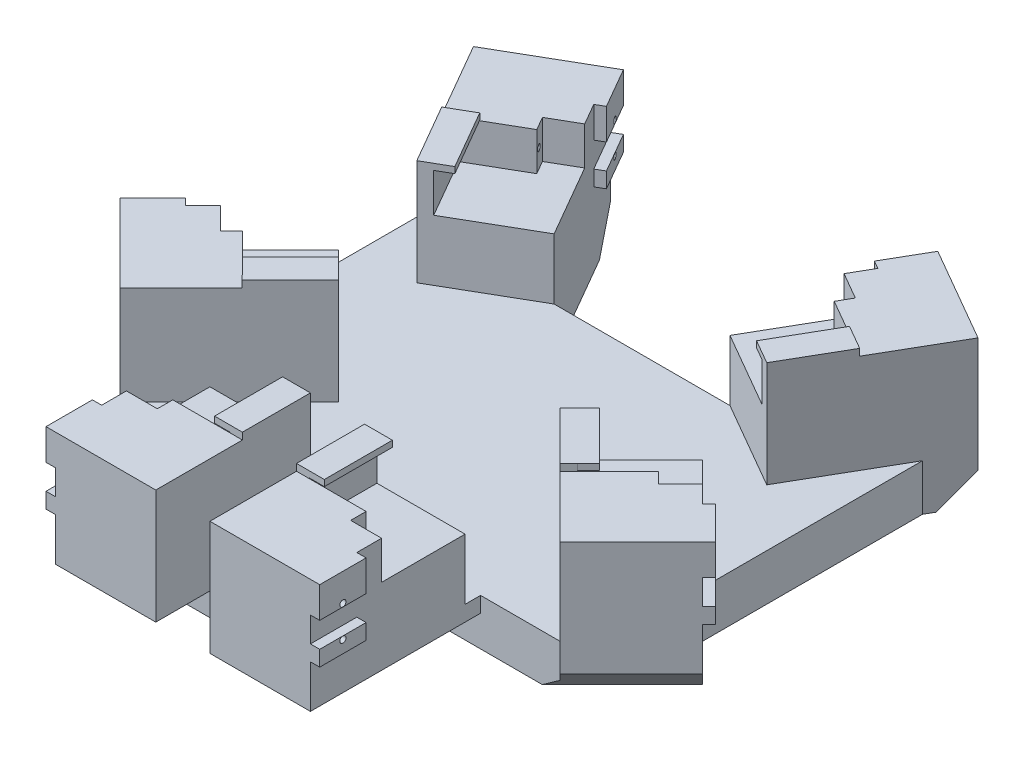
SolidWorks part; units mm, degrees
ref_plane "Front Plane" through (0, 0, 0) normal (0, 0, 1) x (1, 0, 0)
ref_plane "Top Plane" through (0, 0, 0) normal (0, 1, 0) x (1, 0, 0)
ref_plane "Right Plane" through (0, 0, 0) normal (1, 0, 0) x (0, 0, -1)
sketch "Sketch1" plane through (0, 0, 0) normal (0, 1, 0) x (1, 0, 0)
  line L1 (-75, 75) -> (75, 75)
  line L2 (-75, 75) -> (-75, -75)
  line L3 (-75, -75) -> (75, -75)
  line L4 (75, 75) -> (75, -75)
  line L5 (-75, 75) -> (75, -75) construction
  line L6 (-75, -75) -> (75, 75) construction
  point P0 (0, 0)
  dimension "D1" = 150
extrude "Base" add sketch "Sketch1" along normal mid plane 15 contours L2 L3 L4 L1
sketch "Sketch2" plane through (0, 7.5, 0) normal (0, 1, 0) x (1, 0, 0)
  line L0 (0, 93.5371) -> (0, -100.4541) construction
  line L2 (-41.25, -95) -> (-8.75, -95)
  line L3 (-41.25, -95) -> (-41.25, -45)
  line L4 (-41.25, -45) -> (-8.75, -45)
  line L5 (-8.75, -95) -> (-8.75, -45)
  line L6 (-41.25, -95) -> (-8.75, -45) construction
  line L7 (-41.25, -45) -> (-8.75, -95) construction
  line L8 (-75, -75) -> (75, -75) construction
  line L12 (-75, 75) -> (75, 75) construction
  line L13 (-81.5729, 80.5256) -> (-53.4271, 96.7756)
  line L14 (-81.5729, 80.5256) -> (-28.4271, 53.4744) construction
  line L15 (-28.4271, 53.4744) -> (-53.4271, 96.7756)
  line L16 (-56.5729, 37.2244) -> (-28.4271, 53.4744)
  line L17 (-56.5729, 37.2244) -> (-81.5729, 80.5256)
  line L18 (-56.5729, 37.2244) -> (-53.4271, 96.7756) construction
  line L25 (-58.8128, 14.1682) -> (-35.8318, -8.8128)
  line L26 (-58.8128, 14.1682) -> (-71.1872, -44.1682) construction
  line L27 (-71.1872, -44.1682) -> (-35.8318, -8.8128)
  line L28 (-94.1682, -21.1872) -> (-71.1872, -44.1682)
  line L29 (-94.1682, -21.1872) -> (-58.8128, 14.1682)
  line L30 (-94.1682, -21.1872) -> (-35.8318, -8.8128) construction
  line L36 (-75, 75) -> (-75, -75) construction
  point P3 (-25, -70)
  point P13 (-55, 67)
  point P23 (-65, -15)
  dimension "D2" = 32.5
  dimension "D3" = 30
  dimension "D4" = 32.5
  dimension "D5" = 50
  dimension "D6" = 32.5
  dimension "D7" = 50
  dimension "D8" = 130
  dimension "D9" = 60
  dimension "D10" = 50
  dimension "D11" = 30
  dimension "D12" = 110
  dimension "D13" = 45
  dimension "D14" = 8
  dimension "D15" = 50
extrude "ModelServos" add sketch "Sketch2" along normal blind 22 contours L28 L27 L25 L29
mirror "Mirror1" about plane through (0, 0, 0) normal (1, 0, 0) of "ModelServos"
sketch "Sketch3" plane through (0, 7.5, 0) normal (0, 1, 0) x (1, 0, 0)
  line L1 (75, -40) -> (41.25, -40)
  line L2 (75, -40) -> (75, -75)
  line L3 (75, -75) -> (41.25, -75)
  line L4 (41.25, -40) -> (41.25, -75)
  line L6 (41.25, -45) -> (41.25, -75) construction
  line L7 (-75, -75) -> (75, -75) construction
  line L8 (75, -40.3553) -> (75, -75) construction
  dimension "D1" = 35
extrude "Cut-Extrude1" cut sketch "Sketch3" against normal through all
mirror "Mirror2" about plane through (0, 0, 0) normal (1, 0, 0) of "Cut-Extrude1"
sketch "Sketch5" plane through (0, 29.5, 0) normal (0, 1, 0) x (1, 0, 0)
  line L0 (12.75, -45) -> (12.75, -67)
  line L1 (8.75, -45) -> (41.25, -45) construction
  line L2 (12.75, -67) -> (41.25, -67)
  line L3 (41.25, -45) -> (41.25, -95) construction
  line L4 (12.75, -45) -> (41.25, -45)
  line L5 (41.25, -45) -> (41.25, -67)
  dimension "D1" = 22
  dimension "D2" = 28.5
extrude "Cut-Extrude3" cut sketch "Sketch5" against normal blind 2.35
sketch "Sketch6" plane through (0, 29.5, 0) normal (0, 1, 0) x (1, 0, 0)
  line L0 (41.25, -67) -> (41.25, -95) construction
  line L1 (41.25, -80) -> (38.25, -80)
  line L2 (41.25, -80) -> (41.25, -95)
  line L3 (41.25, -95) -> (38.25, -95)
  line L4 (38.25, -80) -> (38.25, -95)
  line L5 (41.25, -95) -> (8.75, -95) construction
  dimension "D1" = 3
  dimension "D2" = 15
extrude "Boss-Extrude1" add sketch "Sketch6" along normal blind 10
sketch "Sketch8" plane through (41.25, 0, 0) normal (1, 0, 0) x (0, 0, -1)
  line L1 (-95, 39.5) -> (-80, 39.5)
  line L2 (-95, 39.5) -> (-95, 29.5)
  line L3 (-95, 29.5) -> (-80, 29.5)
  line L4 (-80, 39.5) -> (-80, 29.5)
extrude "Boss-Extrude2" add sketch "Sketch8" along normal blind 3
sketch "Sketch9" plane through (41.25, 0, 0) normal (1, 0, 0) x (0, 0, -1)
  line L1 (-95, 21.4) -> (-80, 21.4)
  line L2 (-95, 21.4) -> (-95, 16.4)
  line L3 (-95, 16.4) -> (-80, 16.4)
  line L4 (-80, 21.4) -> (-80, 16.4)
  line L6 (-95, 29.5) -> (-95, 7.5) construction
  dimension "D1" = 15
  dimension "D2" = 5
  dimension "D3" = 8.1
extrude "Boss-Extrude3" add sketch "Sketch9" along normal blind 3
sketch "Sketch10" plane through (0, 29.5, 0) normal (0, 1, 0) x (1, 0, 0)
  line L0 (58.8128, 14.1682) -> (38.6603, -5.9844)
  line L1 (35.8318, -8.8128) -> (58.8128, 14.1682) construction
  line L2 (38.6603, -5.9844) -> (54.2166, -21.5407)
  line L3 (54.2166, -21.5407) -> (74.3692, -1.3882)
  line L4 (58.8128, 14.1682) -> (94.1682, -21.1872) construction
  line L5 (74.3692, -1.3882) -> (58.8128, 14.1682)
  dimension "D1" = 28.5
  dimension "D2" = 22
extrude "Cut-Extrude4" cut sketch "Sketch10" against normal blind 2.35
sketch "Sketch11" plane through (0, 29.5, 0) normal (0, 1, 0) x (1, 0, 0)
  line L0 (94.1682, -21.1872) -> (89.9255, -25.4298)
  line L1 (94.1682, -21.1872) -> (71.1872, -44.1682) construction
  line L2 (89.9255, -25.4298) -> (79.3189, -14.8232)
  line L3 (79.3189, -14.8232) -> (83.5616, -10.5806)
  line L4 (74.3692, -1.3882) -> (94.1682, -21.1872) construction
  line L5 (83.5616, -10.5806) -> (94.1682, -21.1872)
  dimension "D1" = 15
  dimension "D2" = 6
extrude "Boss-Extrude4" add sketch "Sketch11" along normal blind 10
sketch "Sketch12" plane through (36.4905, 0, -36.4905) normal (0.7071, 0, -0.7071) x (-0.7071, 0, -0.7071)
  line L1 (-66.5685, 29.5) -> (-81.5685, 29.5)
  line L2 (-66.5685, 29.5) -> (-66.5685, 39.5)
  line L3 (-66.5685, 39.5) -> (-81.5685, 39.5)
  line L4 (-81.5685, 29.5) -> (-81.5685, 39.5)
extrude "Boss-Extrude5" add sketch "Sketch12" along normal blind 3
sketch "Sketch13" plane through (36.4905, 0, -36.4905) normal (0.7071, 0, -0.7071) x (-0.7071, 0, -0.7071)
  line L0 (-81.5685, 29.5) -> (-81.5685, 7.5) construction
  line L1 (-81.5685, 21.4) -> (-66.5685, 21.4)
  line L2 (-81.5685, 21.4) -> (-81.5685, 16.4)
  line L3 (-81.5685, 16.4) -> (-66.5685, 16.4)
  line L4 (-66.5685, 21.4) -> (-66.5685, 16.4)
  dimension "D1" = 15
  dimension "D2" = 5
  dimension "D3" = 8.1
extrude "Boss-Extrude6" add sketch "Sketch13" along normal blind 3
sketch "Sketch14" plane through (0, 7.5, 0) normal (0, 1, 0) x (1, 0, 0)
  line L0 (-28.4271, 53.4744) -> (28.4271, 53.4744)
  line L1 (28.4271, 53.4744) -> (40.8549, 75)
  line L2 (40.8549, 75) -> (-40.8549, 75)
  line L3 (-40.8549, 75) -> (-28.4271, 53.4744)
extrude "Cut-Extrude5" cut sketch "Sketch14" against normal through all
sketch "Sketch15" plane through (0, 29.5, 0) normal (0, 1, 0) x (1, 0, 0)
  line L0 (28.4271, 53.4744) -> (39.4271, 72.5269)
  line L1 (28.4271, 53.4744) -> (53.4271, 96.7756) construction
  line L2 (39.4271, 72.5269) -> (64.1088, 58.2769)
  line L3 (64.1088, 58.2769) -> (53.1088, 39.2244)
  line L4 (56.5729, 37.2244) -> (28.4271, 53.4744) construction
  line L5 (53.1088, 39.2244) -> (28.4271, 53.4744)
  dimension "D1" = 22
  dimension "D2" = 28.5
extrude "Cut-Extrude6" cut sketch "Sketch15" against normal blind 2.35
sketch "Sketch16" plane through (0, 29.5, 0) normal (0, 1, 0) x (1, 0, 0)
  line L0 (53.4271, 96.7756) -> (58.6232, 93.7756)
  line L1 (53.4271, 96.7756) -> (81.5729, 80.5256) construction
  line L2 (58.6232, 93.7756) -> (51.1232, 80.7853)
  line L3 (51.1232, 80.7853) -> (45.9271, 83.7853)
  line L4 (39.4271, 72.5269) -> (53.4271, 96.7756) construction
  line L5 (45.9271, 83.7853) -> (53.4271, 96.7756)
  dimension "D1" = 15
  dimension "D2" = 6
extrude "Boss-Extrude7" add sketch "Sketch16" along normal blind 10
sketch "Sketch17" plane through (-1.8348, 0, -1.0593) normal (-0.866, 0, -0.5) x (-0.5, 0, 0.866)
  line L1 (-95.5237, 29.5) -> (-110.5237, 29.5)
  line L2 (-95.5237, 29.5) -> (-95.5237, 39.5)
  line L3 (-95.5237, 39.5) -> (-110.5237, 39.5)
  line L4 (-110.5237, 29.5) -> (-110.5237, 39.5)
extrude "Boss-Extrude8" add sketch "Sketch17" along normal blind 3
sketch "Sketch18" plane through (-1.8348, 0, -1.0593) normal (-0.866, 0, -0.5) x (-0.5, 0, 0.866)
  line L0 (-110.5237, 29.5) -> (-110.5237, 7.5) construction
  line L1 (-110.5237, 21.4) -> (-95.5237, 21.4)
  line L2 (-110.5237, 21.4) -> (-110.5237, 16.4)
  line L3 (-110.5237, 16.4) -> (-95.5237, 16.4)
  line L4 (-95.5237, 21.4) -> (-95.5237, 16.4)
  dimension "D1" = 15
  dimension "D2" = 5
  dimension "D3" = 8.1
extrude "Boss-Extrude9" add sketch "Sketch18" along normal blind 3
sketch "Sketch20" plane through (0, 29.5, 0) normal (0, 1, 0) x (1, 0, 0)
  line L12 (41.25, -67) -> (12.75, -67)
  line L17 (12.75, -67) -> (12.75, -45)
  line L18 (12.75, -45) -> (8.75, -45)
  line L19 (8.75, -45) -> (8.75, -95)
  line L20 (8.75, -95) -> (38.25, -95)
  line L21 (38.25, -95) -> (38.25, -80)
  line L22 (38.25, -80) -> (41.25, -80)
  line L23 (41.25, -80) -> (41.25, -67)
  line L24 (41.25, -67) -> (12.75, -67)
  line L29 (12.75, -67) -> (12.75, -45)
  line L30 (12.75, -45) -> (8.75, -45)
  line L31 (8.75, -45) -> (8.75, -95)
  line L32 (8.75, -95) -> (38.25, -95)
  line L33 (38.25, -95) -> (38.25, -80)
  line L34 (38.25, -80) -> (41.25, -80)
  line L35 (41.25, -80) -> (41.25, -67)
  dimension "D1" = 0
extrude "Boss-Extrude10" add sketch "Sketch20" along normal up to surface (10 mm away) up to face at (41.25, 39.5, 87.5)
sketch "Sketch22" plane through (0, 29.5, 0) normal (0, 1, 0) x (1, 0, 0)
  line L12 (74.3692, -1.3882) -> (54.2166, -21.5407)
  line L17 (54.2166, -21.5407) -> (38.6603, -5.9844)
  line L18 (38.6603, -5.9844) -> (35.8318, -8.8128)
  line L19 (35.8318, -8.8128) -> (71.1872, -44.1682)
  line L20 (71.1872, -44.1682) -> (89.9255, -25.4298)
  line L21 (89.9255, -25.4298) -> (79.3189, -14.8232)
  line L22 (79.3189, -14.8232) -> (83.5616, -10.5806)
  line L23 (83.5616, -10.5806) -> (74.3692, -1.3882)
  line L24 (74.3692, -1.3882) -> (54.2166, -21.5407)
  line L29 (54.2166, -21.5407) -> (38.6603, -5.9844)
  line L30 (38.6603, -5.9844) -> (35.8318, -8.8128)
  line L31 (35.8318, -8.8128) -> (71.1872, -44.1682)
  line L32 (71.1872, -44.1682) -> (89.9255, -25.4298)
  line L33 (89.9255, -25.4298) -> (79.3189, -14.8232)
  line L34 (79.3189, -14.8232) -> (83.5616, -10.5806)
  line L35 (83.5616, -10.5806) -> (74.3692, -1.3882)
  dimension "D1" = 0
extrude "Boss-Extrude11" add sketch "Sketch22" along normal up to surface (10 mm away) up to face at (87.8042, 39.5, 16.9445)
sketch "Sketch24" plane through (0, 29.5, 0) normal (0, 1, 0) x (1, 0, 0)
  line L14 (39.4271, 72.5269) -> (64.1088, 58.2769)
  line L15 (64.1088, 58.2769) -> (53.1088, 39.2244)
  line L16 (53.1088, 39.2244) -> (56.5729, 37.2244)
  line L17 (56.5729, 37.2244) -> (81.5729, 80.5256)
  line L18 (81.5729, 80.5256) -> (58.6232, 93.7756)
  line L19 (58.6232, 93.7756) -> (51.1232, 80.7853)
  line L20 (51.1232, 80.7853) -> (45.9271, 83.7853)
  line L21 (45.9271, 83.7853) -> (39.4271, 72.5269)
  line L26 (39.4271, 72.5269) -> (64.1088, 58.2769)
  line L27 (64.1088, 58.2769) -> (53.1088, 39.2244)
  line L28 (53.1088, 39.2244) -> (56.5729, 37.2244)
  line L29 (56.5729, 37.2244) -> (81.5729, 80.5256)
  line L30 (81.5729, 80.5256) -> (58.6232, 93.7756)
  line L31 (58.6232, 93.7756) -> (51.1232, 80.7853)
  line L32 (51.1232, 80.7853) -> (45.9271, 83.7853)
  line L33 (45.9271, 83.7853) -> (39.4271, 72.5269)
  dimension "D1" = 0
extrude "Boss-Extrude12" add sketch "Sketch24" along normal up to surface (10 mm away) up to face at (50.9761, 39.5, -89.5304)
sketch "Sketch27" plane through (0, 7.5, 0) normal (0, -1, 0) x (1, 0, 0)
  line L4 (8.75, 75) -> (41.25, 75)
  line L5 (41.25, 75) -> (41.25, 95)
  line L6 (41.25, 95) -> (8.75, 95)
  line L7 (8.75, 95) -> (8.75, 75)
  line L8 (8.75, 75) -> (41.25, 75)
  line L9 (41.25, 75) -> (41.25, 95)
  line L10 (41.25, 95) -> (8.75, 95)
  line L11 (8.75, 95) -> (8.75, 75)
  dimension "D1" = 0
extrude "Boss-Extrude15" add sketch "Sketch27" along normal up to surface (15 mm away) up to face at (0, -7.5, -8.0791)
sketch "Sketch26" plane through (0, 7.5, 0) normal (0, -1, 0) x (1, 0, 0)
  line L3 (94.1682, 21.1872) -> (71.1872, 44.1682)
  line L4 (75, 40) -> (75, 2.019)
  line L5 (75, 2.019) -> (94.1682, 21.1872)
  line L6 (94.1682, 21.1872) -> (71.1872, 44.1682)
  line L7 (75, 40) -> (75, 2.019)
  line L8 (75, 2.019) -> (94.1682, 21.1872)
  line L11 (71.1872, 44.1682) -> (67.019, 40)
  line L15 (71.1872, 44.1682) -> (67.019, 40)
  line L17 (67.019, 40) -> (75, 40)
  line L18 (67.019, 40) -> (75, 40)
  dimension "D1" = 0
extrude "Boss-Extrude14" add sketch "Sketch26" along normal up to surface (15 mm away) up to face at (1.25, -7.5, 6.6465)
sketch "Sketch25" plane through (0, 7.5, 0) normal (0, -1, 0) x (1, 0, 0)
  line L5 (75, -69.141) -> (75, -75)
  line L6 (75, -75) -> (40.8549, -75)
  line L7 (40.8549, -75) -> (53.4271, -96.7756)
  line L8 (53.4271, -96.7756) -> (81.5729, -80.5256)
  line L9 (81.5729, -80.5256) -> (75, -69.141)
  line L10 (75, -69.141) -> (75, -75)
  line L11 (75, -75) -> (40.8549, -75)
  line L12 (40.8549, -75) -> (53.4271, -96.7756)
  line L13 (53.4271, -96.7756) -> (81.5729, -80.5256)
  line L14 (81.5729, -80.5256) -> (75, -69.141)
  dimension "D1" = 0
extrude "Boss-Extrude13" add sketch "Sketch25" along normal up to surface (15 mm away) up to face at (14.6985, -7.5, 9.4368)
sketch "Sketch43" plane through (41.25, 0, 0) normal (1, 0, 0) x (0, 0, -1)
  line L0 (-67, 27.15) -> (-45, 27.15) construction
  line L1 (-67, 39.5) -> (-72, 39.5)
  line L2 (-67, 39.5) -> (-67, 27.15)
  line L3 (-67, 27.15) -> (-72, 27.15)
  line L4 (-72, 39.5) -> (-72, 27.15)
  dimension "D1" = 5
extrude "Cut-Extrude15" cut sketch "Sketch43" against normal blind 10
sketch "Sketch37" plane through (31.25, 0, 0) normal (1, 0, 0) x (0, 0, -1)
  line L0 (-67, 27.15) -> (-67, 39.5) construction
  line L2 (-72, 27.15) -> (-67, 27.15) construction
  circle A0 centre (-68.9, 33.15) radius 1
  dimension "D1" = 2
  dimension "D2" = 1.9
  dimension "D3" = 6
extrude "Cut-Extrude7" cut sketch "Sketch37" against normal blind 5
sketch "Sketch38" plane through (44.25, 0, 0) normal (1, 0, 0) x (0, 0, -1)
  line L2 (-95, 29.5) -> (-80, 29.5) construction
  line L4 (-80, 21.4) -> (-95, 21.4) construction
  circle A0 centre (-87.5, 30.51) radius 1
  circle A1 centre (-87.5, 20.39) radius 1
  point P2 (-87.5, 29.5)
  point P9 (0, 0)
  point P10 (-87.5, 20.1416)
  dimension "D1" = 2
  dimension "D3" = 1.01
  dimension "D2" = 1.01
extrude "Cut-Extrude10" cut sketch "Sketch38" against normal blind 5
sketch "Sketch44" plane through (36.4905, 0, -36.4905) normal (0.7071, 0, -0.7071) x (-0.7071, 0, -0.7071)
  line L0 (-53.5685, 27.15) -> (-31.5685, 27.15) construction
  line L1 (-53.5685, 39.5) -> (-58.5685, 39.5)
  line L2 (-53.5685, 39.5) -> (-53.5685, 27.15)
  line L3 (-53.5685, 27.15) -> (-58.5685, 27.15)
  line L4 (-58.5685, 39.5) -> (-58.5685, 27.15)
  dimension "D1" = 5
extrude "Cut-Extrude16" cut sketch "Sketch44" against normal blind 10
sketch "Sketch39" plane through (29.4194, 0, -29.4194) normal (0.7071, 0, -0.7071) x (-0.7071, 0, -0.7071)
  line L0 (-53.5685, 27.15) -> (-53.5685, 39.5) construction
  circle A0 centre (-55.4685, 33.15) radius 1
  dimension "D1" = 2
  dimension "D2" = 1.9
  dimension "D3" = 6
extrude "Cut-Extrude11" cut sketch "Sketch39" against normal blind 5
sketch "Sketch40" plane through (38.6118, 0, -38.6118) normal (0.7071, 0, -0.7071) x (-0.7071, 0, -0.7071)
  line L0 (-81.5685, 29.5) -> (-66.5685, 29.5) construction
  line L1 (-66.5685, 21.4) -> (-81.5685, 21.4) construction
  circle A0 centre (-74.0685, 30.51) radius 1
  circle A1 centre (-74.0685, 20.39) radius 1
  point P6 (-74.0685, 29.5)
  point P11 (0, 0)
  dimension "D1" = 2
  dimension "D3" = 2
  dimension "D2" = 1.01
  dimension "D4" = 1.01
extrude "Cut-Extrude12" cut sketch "Sketch40" against normal blind 5
sketch "Sketch45" plane through (-1.8348, 0, -1.0593) normal (-0.866, 0, -0.5) x (-0.5, 0, 0.866)
  line L0 (-82.5237, 27.15) -> (-60.5237, 27.15) construction
  line L1 (-82.5237, 39.5) -> (-87.5237, 39.5)
  line L2 (-82.5237, 39.5) -> (-82.5237, 27.15)
  line L3 (-82.5237, 27.15) -> (-87.5237, 27.15)
  line L4 (-87.5237, 39.5) -> (-87.5237, 27.15)
  dimension "D1" = 5
extrude "Cut-Extrude17" cut sketch "Sketch45" against normal blind 10
sketch "Sketch41" plane through (6.8255, 0, 3.9407) normal (-0.866, 0, -0.5) x (-0.5, 0, 0.866)
  line L0 (-82.5237, 27.15) -> (-82.5237, 39.5) construction
  circle A0 centre (-84.4237, 33.15) radius 1
  dimension "D1" = 2
  dimension "D2" = 1.9
  dimension "D3" = 6
extrude "Cut-Extrude13" cut sketch "Sketch41" against normal blind 5
sketch "Sketch42" plane through (-4.4328, 0, -2.5593) normal (-0.866, 0, -0.5) x (-0.5, 0, 0.866)
  line L0 (-110.5237, 29.5) -> (-95.5237, 29.5) construction
  line L1 (-95.5237, 21.4) -> (-110.5237, 21.4) construction
  circle A0 centre (-103.0237, 30.51) radius 1
  circle A1 centre (-103.0237, 20.39) radius 1
  point P6 (-103.0237, 29.5)
  point P9 (0, 0)
  dimension "D1" = 2
  dimension "D3" = 2
  dimension "D2" = 1.01
  dimension "D4" = 1.01
extrude "Cut-Extrude14" cut sketch "Sketch42" against normal blind 5
mirror "Mirror4" about plane through (0, 0, 0) normal (1, 0, 0) of "Cut-Extrude17", "Cut-Extrude16", "Cut-Extrude15", "Cut-Extrude10", "Cut-Extrude7", "Cut-Extrude3", "Boss-Extrude1", "Boss-Extrude2", "Boss-Extrude3", "Cut-Extrude4", "Boss-Extrude4", "Boss-Extrude5", "Boss-Extrude6", "Cut-Extrude6", "Boss-Extrude7", "Boss-Extrude8", "Boss-Extrude9", "Boss-Extrude10", "Boss-Extrude11", "Boss-Extrude12", "Cut-Extrude11", "Cut-Extrude12", "Cut-Extrude13", "Cut-Extrude14"
mirror "Mirror5" about plane through (0, 0, 0) normal (1, 0, 0) of "Boss-Extrude13", "Boss-Extrude15", "Boss-Extrude14"
chamfer "Chamfer1" distance 10 angle 45 11 edges at (41.25, -7.5, 67.5) (-41.25, -7.5, 67.5) (25, -7.5, 95) (82.6777, -7.5, 32.6777) (69.1031, -7.5, 42.0841) (67.5, -7.5, -88.6506) (-25, -7.5, 95) (-8.75, -7.5, 85) (-82.6777, -7.5, 32.6777) (-69.1031, -7.5, 42.0841) (-67.5, -7.5, -88.6506)
sketch "Sketch28" plane through (0, 7.5, 0) normal (0, 1, 0) x (1, 0, 0)
  line L1 (-12.8, -31.35) -> (12.8, -31.35)
  line L2 (-12.8, -31.35) -> (-12.8, 31.35)
  line L3 (-12.8, 31.35) -> (12.8, 31.35)
  line L4 (12.8, -31.35) -> (12.8, 31.35)
  line L5 (-12.8, -31.35) -> (12.8, 31.35) construction
  line L6 (-12.8, 31.35) -> (12.8, -31.35) construction
  point P0 (0, 0)
  dimension "D1" = 62.7
  dimension "D2" = 25.6
extrude "Extrude-Thin1" [suppressed] add sketch "Sketch28" along normal blind 2 thin
fillet "Fillet1" [suppressed] radius 1
sketch "Sketch29" [suppressed] plane through (0, 31.5, 0) normal (0, 1, 0) x (1, 0, 0)
  line L1 (4.8092, -41.3868) -> (48.4281, -41.3868)
  line L2 (4.8092, -41.3868) -> (4.8092, -99.4832)
  line L3 (4.8092, -99.4832) -> (48.4281, -99.4832)
  line L4 (48.4281, -41.3868) -> (48.4281, -99.4832)
extrude "Test" [suppressed] cut sketch "Sketch29" against normal through all flip side to cut
sketch "Sketch30" plane through (0, 39.5, 0) normal (0, 1, 0) x (1, 0, 0)
  line L1 (12.75, -67) -> (8.75, -67)
  line L2 (12.75, -67) -> (12.75, -45)
  line L3 (12.75, -45) -> (8.75, -45)
  line L4 (8.75, -67) -> (8.75, -45)
extrude "10.2mm" add sketch "Sketch30" along normal blind 2.2
sketch "Sketch31" plane through (12.75, 0, 0) normal (1, 0, 0) x (0, 0, -1)
  line L1 (-45, 39.7) -> (-67, 39.7)
  line L2 (-45, 39.7) -> (-45, 41.7)
  line L3 (-45, 41.7) -> (-67, 41.7)
  line L4 (-67, 39.7) -> (-67, 41.7)
  line L7 (-45, 27.15) -> (-45, 41.7) construction
  dimension "D1" = 2
extrude "2 x 5 mm" add sketch "Sketch31" along normal blind 5
sketch "Sketch32" plane through (0, 39.5, 0) normal (0, 1, 0) x (1, 0, 0)
  line L0 (54.2166, -21.5407) -> (51.4254, -24.4064)
  line L1 (67.019, -40) -> (35.8318, -8.8128) construction
  line L2 (51.4254, -24.4064) -> (35.8318, -8.8128)
  line L3 (35.8318, -8.8128) -> (38.6603, -5.9844)
  line L4 (38.6603, -5.9844) -> (54.2166, -21.5407)
extrude "Boss-Extrude16" add sketch "Sketch32" along normal blind 2.2
sketch "Sketch33" plane through (16.3379, 0, -16.3379) normal (0.7071, 0, -0.7071) x (-0.7071, 0, -0.7071)
  line L0 (-31.5685, 27.15) -> (-31.5685, 41.7) construction
  line L1 (-53.5685, 41.7) -> (-31.5685, 41.7)
  line L2 (-53.5685, 41.7) -> (-53.5685, 39.7)
  line L3 (-53.5685, 39.7) -> (-31.5685, 39.7)
  line L4 (-31.5685, 41.7) -> (-31.5685, 39.7)
  dimension "D1" = 2
extrude "Boss-Extrude17" add sketch "Sketch33" along normal blind 5
sketch "Sketch34" plane through (0, 39.5, 0) normal (0, 1, 0) x (1, 0, 0)
  line L0 (64.1088, 58.2769) -> (67.5729, 56.2769)
  line L1 (75, 69.141) -> (56.5729, 37.2244) construction
  line L2 (67.5729, 56.2769) -> (56.5729, 37.2244)
  line L3 (56.5729, 37.2244) -> (53.1088, 39.2244)
  line L4 (53.1088, 39.2244) -> (64.1088, 58.2769)
extrude "Boss-Extrude18" add sketch "Sketch34" along normal blind 2.2
sketch "Sketch35" plane through (22.847, 0, 13.1907) normal (-0.866, 0, -0.5) x (-0.5, 0, 0.866)
  line L0 (-60.5237, 27.15) -> (-60.5237, 41.7) construction
  line L1 (-82.5237, 41.7) -> (-60.5237, 41.7)
  line L2 (-82.5237, 41.7) -> (-82.5237, 39.7)
  line L3 (-82.5237, 39.7) -> (-60.5237, 39.7)
  line L4 (-60.5237, 41.7) -> (-60.5237, 39.7)
  dimension "D1" = 2
extrude "Boss-Extrude19" add sketch "Sketch35" along normal blind 5
mirror "Mirror6" about plane through (0, 0, 0) normal (1, 0, 0) of "2 x 5 mm", "10.2mm", "Boss-Extrude16", "Boss-Extrude17", "Boss-Extrude18", "Boss-Extrude19"
